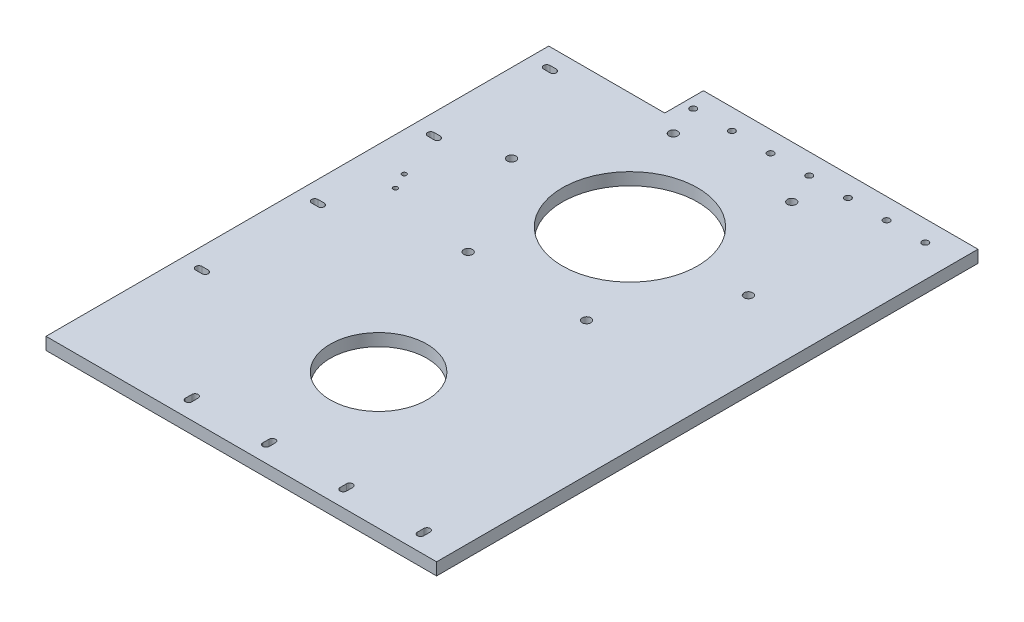
SolidWorks part; units mm, degrees
ref_plane "Front Plane" through (0, 0, 0) normal (0, 0, 1) x (1, 0, 0)
ref_plane "Top Plane" through (0, 0, 0) normal (0, 1, 0) x (1, 0, 0)
ref_plane "Right Plane" through (0, 0, 0) normal (1, 0, 0) x (0, 0, -1)
sketch "Sketch1" plane through (0, 0, 0) normal (0, 1, 0) x (1, 0, 0)
  line L3 (-71, 140) -> (71, 140)
  line L4 (71, -140) -> (71, 140)
  line L5 (0, 140) -> (0, -135) construction
  line L6 (0, 0) -> (71, 0) construction
  line L10 (-71, 140) -> (-71, 120)
  line L11 (-71, 120) -> (-131, 120)
  line L12 (-131, 120) -> (-131, -140)
  line L13 (-131, -140) -> (71, -140)
  point P0 (0, 0)
  dimension "D1" = 280
  dimension "D2" = 20
  dimension "D3" = 202
  dimension "D4" = 60
extrude "Boss-Extrude1" add sketch "Sketch1" along normal blind 6.35
sketch "Sketch2" plane through (0, 6.35, 0) normal (0, 1, 0) x (1, 0, 0)
  line L1 (0, 140) -> (0, -140) construction
  line L2 (71, 140) -> (-71, 140) construction
  line L3 (-131, -140) -> (71, -140) construction
  circle A0 centre (0, -65) radius 41.5 construction
  circle A1 centre (0, -23.5) radius 2.25
  circle A2 centre (29.3449, -35.6551) radius 2.25
  circle A3 centre (41.5, -65) radius 2.25
  circle A4 centre (29.3449, -94.3449) radius 2.25
  circle A5 centre (0, -106.5) radius 2.25
  circle A6 centre (-29.3449, -94.3449) radius 2.25
  circle A7 centre (-41.5, -65) radius 2.25
  circle A8 centre (-29.3449, -35.6551) radius 2.25
  circle A9 centre (0, -65) radius 80 construction
  circle A10 centre (0, -65) radius 30
  point P22 (0, -65)
  dimension "D1" = 83
  dimension "D2" = 4.5
  dimension "D4" = 160
  dimension "D6" = 60
  dimension "D5" = 75
  dimension "D3" = 8
extrude "Cut-Extrude1" [suppressed] cut sketch "Sketch2" against normal through all
sketch "Sketch6" [suppressed] plane through (0, 6.35, 0) normal (0, 1, 0) x (1, 0, 0)
  line L0 (0, -65) -> (-38.9712, -46.8274) construction
  line L1 (0, -65) -> (0, -23.5) construction
  line L2 (-40.9787, -51.1324) -> (-36.9638, -42.5225) construction
  line L3 (-36.9638, -42.5225) -> (-27.9007, -46.7486) construction
  circle A0 centre (0, -65) radius 30 construction
  circle A1 centre (-36.9638, -42.5225) radius 0.85
  circle A2 centre (-40.9787, -51.1324) radius 0.85
  circle A5 centre (-29.9082, -51.0536) radius 0.85
  point P7 (-38.9712, -46.8274)
  dimension "D4" = 1.7
  dimension "D5" = 10
  dimension "D7" = 10
  dimension "D6" = 1.7
  dimension "D1" = 43
  dimension "D2" = 9.5
  dimension "D3" = 65
extrude "Cut-Extrude5" [suppressed] cut sketch "Sketch6" against normal through all
sketch "Sketch8" [suppressed] plane through (0, 6.35, 0) normal (0, 1, 0) x (1, 0, 0)
  line L1 (71, 140) -> (-71, 140) construction
  line L2 (65, -20.6305) -> (65, 140) construction
  line L3 (71, -140) -> (71, 140) construction
  line L5 (45, 41.8036) -> (45, 140) construction
  circle A0 centre (0, 65) radius 25
  circle A1 centre (0, -65) radius 30 construction
  dimension "D1" = 130
  dimension "D2" = 50
  dimension "D3" = 6
  dimension "D4" = 20
extrude "Cut-Extrude9" [suppressed] cut sketch "Sketch8" against normal through all
sketch "Sketch9" plane through (0, 0, 0) normal (0, -1, 0) x (-1, 0, 0)
  circle A1 centre (45.6, 129.325) radius 1.65
  circle A2 centre (5.6, 129.325) radius 1.65
  circle A3 centre (-34.4, 129.325) radius 1.65
  circle A4 centre (65.6, 129.325) radius 1.65
  circle A5 centre (25.6, 129.325) radius 1.65
  circle A6 centre (-14.4, 129.325) radius 1.65
  circle A7 centre (-54.4, 129.325) radius 1.65
extrude "Cut-Extrude10" cut sketch "Sketch9" against normal blind 30
sketch "Sketch10" plane through (0, 0, 0) normal (0, -1, 0) x (1, 0, 0)
  line L0 (-121.975, 10) -> (-118.675, 10) construction
  line L3 (-121.975, 11.65) -> (-118.675, 11.65)
  line L4 (-121.975, 8.35) -> (-118.675, 8.35)
  line L5 (-121.975, 70) -> (-118.675, 70) construction
  line L6 (-121.975, 71.65) -> (-118.675, 71.65)
  line L7 (-121.975, 68.35) -> (-118.675, 68.35)
  line L8 (-121.975, -50) -> (-118.675, -50) construction
  line L9 (-121.975, -48.35) -> (-118.675, -48.35)
  line L10 (-121.975, -51.65) -> (-118.675, -51.65)
  line L11 (-121.975, -110) -> (-118.675, -110) construction
  line L12 (-121.975, -108.35) -> (-118.675, -108.35)
  line L13 (-121.975, -111.65) -> (-118.675, -111.65)
  circle A0 centre (-120.325, -110) radius 1.65
  circle A1 centre (-120.325, -50) radius 1.65
  circle A2 centre (-120.325, 10) radius 1.65
  circle A3 centre (-120.325, 70) radius 1.65
  arc A6 (-121.975, 11.65) -> (-121.975, 8.35) centre (-121.975, 10) ccw
  arc A7 (-118.675, 8.35) -> (-118.675, 11.65) centre (-118.675, 10) ccw
  arc A8 (-121.975, 71.65) -> (-121.975, 68.35) centre (-121.975, 70) ccw
  arc A9 (-118.675, 68.35) -> (-118.675, 71.65) centre (-118.675, 70) ccw
  arc A10 (-121.975, -48.35) -> (-121.975, -51.65) centre (-121.975, -50) ccw
  arc A11 (-118.675, -51.65) -> (-118.675, -48.35) centre (-118.675, -50) ccw
  arc A12 (-121.975, -108.35) -> (-121.975, -111.65) centre (-121.975, -110) ccw
  arc A13 (-118.675, -111.65) -> (-118.675, -108.35) centre (-118.675, -110) ccw
  point P14 (-120.325, 10)
  point P21 (-120.325, 70)
  point P28 (-120.325, -50)
  point P35 (-120.325, -110)
  dimension "D1" = 3.3
  dimension "D2" = 3.3
  dimension "D3" = 3.3
  dimension "D4" = 3.3
  dimension "D5" = 1.65
  dimension "D6" = 1.65
  dimension "D7" = 1.65
  dimension "D8" = 1.65
sketch "Sketch11" plane through (0, 6.35, 0) normal (0, 1, 0) x (1, 0, 0)
  line L0 (71, -127.15) -> (-131, -127.15) construction
  line L1 (71, -140) -> (71, 140) construction
  line L2 (456.625, -127.15) -> (-127.825, -127.15) construction
  line L3 (-131, 120) -> (-131, -140) construction
  line L4 (71, -132.85) -> (-131, -132.85) construction
  line L5 (456.625, -132.85) -> (-127.825, -132.85) construction
  line L6 (-65.6, 129.325) -> (-65.6, -130.005) construction
  line L7 (-65.6, -130.005) -> (71, -130) construction
  line L8 (456.625, -130) -> (-127.825, -130) construction
  line L9 (-25.6, 129.325) -> (-25.6, -130.0035) construction
  line L10 (14.4, 129.325) -> (14.4, -130.0021) construction
  line L11 (54.4, 129.325) -> (54.4, -130.0006) construction
  line L12 (-65.6, -128.355) -> (-65.6, -131.655) construction
  line L13 (-63.95, -128.355) -> (-63.95, -131.655)
  line L14 (-67.25, -128.355) -> (-67.25, -131.655)
  line L15 (-25.6, -128.3535) -> (-25.6, -131.6535) construction
  line L16 (-23.95, -128.3535) -> (-23.95, -131.6535)
  line L17 (-27.25, -128.3535) -> (-27.25, -131.6535)
  line L18 (14.4, -128.3521) -> (14.4, -131.6521) construction
  line L19 (16.05, -128.3521) -> (16.05, -131.6521)
  line L20 (12.75, -128.3521) -> (12.75, -131.6521)
  line L21 (54.4, -128.3506) -> (54.4, -131.6506) construction
  line L22 (56.05, -128.3506) -> (56.05, -131.6506)
  line L23 (52.75, -128.3506) -> (52.75, -131.6506)
  circle A0 centre (-65.6, -130.005) radius 1.65 construction
  circle A1 centre (-25.6, -130.0035) radius 1.65 construction
  circle A2 centre (14.4, -130.0021) radius 1.65 construction
  circle A3 centre (54.4, -130.0006) radius 1.65 construction
  arc A4 (-63.95, -128.355) -> (-67.25, -128.355) centre (-65.6, -128.355) ccw
  arc A5 (-67.25, -131.655) -> (-63.95, -131.655) centre (-65.6, -131.655) ccw
  arc A6 (-23.95, -128.3535) -> (-27.25, -128.3535) centre (-25.6, -128.3535) ccw
  arc A7 (-27.25, -131.6535) -> (-23.95, -131.6535) centre (-25.6, -131.6535) ccw
  arc A8 (16.05, -128.3521) -> (12.75, -128.3521) centre (14.4, -128.3521) ccw
  arc A9 (12.75, -131.6521) -> (16.05, -131.6521) centre (14.4, -131.6521) ccw
  arc A10 (56.05, -128.3506) -> (52.75, -128.3506) centre (54.4, -128.3506) ccw
  arc A11 (52.75, -131.6506) -> (56.05, -131.6506) centre (54.4, -131.6506) ccw
  point P33 (-65.6, -130.005)
  point P39 (-25.6, -130.0035)
  point P46 (14.4, -130.0021)
  point P53 (54.4, -130.0006)
  dimension "D2" = 3.3
  dimension "D1" = 259.33
extrude "Cut-Extrude12" cut sketch "Sketch11" against normal blind 30
extrude "Cut-Extrude13" cut sketch "Sketch10" against normal blind 10 contours A0 | L13 A13 L12 A0 | L12 A12 L13 A0 | L9 A10 L10 A1 | A1 | L10 A11 L9 A1 | L3 A6 L4 A2 | A2 | L4 A7 L3 A2 | L6 A8 L7 A3 | A3 | L7 A9 L6 A3
sketch "Sketch12" plane through (0, 6.35, 0) normal (0, 1, 0) x (1, 0, 0)
  line L0 (-131, -140) -> (71, -140) construction
  line L1 (71, -140) -> (71, 140) construction
  circle A0 centre (-29, 60) radius 35
  dimension "D1" = 70
  dimension "D2" = 200
  dimension "D3" = 100
extrude "Cut-Extrude14" cut sketch "Sketch12" against normal through all
sketch "Sketch13" plane through (0, 6.35, 0) normal (0, 1, 0) x (1, 0, 0)
  line L0 (-96.5, 60) -> (-84, 60) construction
  circle A2 centre (-29, 60) radius 67.5 construction
  circle A3 centre (-90.25, 60) radius 2.25
  circle A4 centre (-59.625, 113.0441) radius 2.25
  circle A5 centre (-29, 60) radius 67.5 construction
  circle A6 centre (1.625, 113.0441) radius 2.25
  circle A7 centre (-29, 60) radius 67.5 construction
  circle A8 centre (32.25, 60) radius 2.25
  circle A9 centre (-29, 60) radius 67.5 construction
  circle A10 centre (1.625, 6.9559) radius 2.25
  circle A11 centre (-29, 60) radius 67.5 construction
  circle A12 centre (-59.625, 6.9559) radius 2.25
  circle A13 centre (-29, 60) radius 67.5 construction
  circle A14 centre (-29, 60) radius 55 construction
  circle A15 centre (-29, 60) radius 35 construction
  point P25 (-29, 60)
  dimension "D1" = 135
  dimension "D2" = 4.5
  dimension "D3" = 6
  dimension "D4" = 110
extrude "Cut-Extrude15" cut sketch "Sketch13" against normal through all
sketch "Sketch14" plane through (0, 6.35, 0) normal (0, 1, 0) x (1, 0, 0)
  circle A0 centre (-29, -70) radius 25
  circle A1 centre (-29, 60) radius 35 construction
  circle A2 centre (-29, 60) radius 35 construction
  dimension "D1" = 50
  dimension "D2" = 130
extrude "Cut-Extrude16" cut sketch "Sketch14" against normal blind 10
sketch "Sketch15" plane through (0, 6.35, 0) normal (0, 1, 0) x (1, 0, 0)
  line L0 (-111.0245, 25.2989) -> (-106.9837, 16.7011) construction
  line L1 (-94.5, -140) -> (-94.5, 120) construction
  line L2 (-131, 120) -> (-131, -140) construction
  line L3 (-71, 120) -> (-131, 120) construction
  line L4 (-131, -140) -> (71, -140) construction
  line L5 (-94.5, 26) -> (-131, 26) construction
  line L6 (-94.5, 16) -> (-131, 16) construction
  line L7 (-131, 26) -> (-131, 16) construction
  line L8 (-99.1997, 26) -> (-94.5, 16) construction
  circle A0 centre (-111.0245, 25.2989) radius 1.175
  circle A1 centre (-106.9837, 16.7011) radius 1.175
  circle A2 centre (-29, 60) radius 78 construction
  circle A3 centre (-29, 60) radius 35 construction
  point P18 (-109.0041, 21)
  point P19 (-131, 21)
  dimension "D1" = 2.35
  dimension "D2" = 9.5
  dimension "D3" = 11
  dimension "D7" = 156
  dimension "D4" = 36.5
  dimension "D5" = 94
  dimension "D6" = 10
extrude "Cut-Extrude17" cut sketch "Sketch15" against normal blind 10
